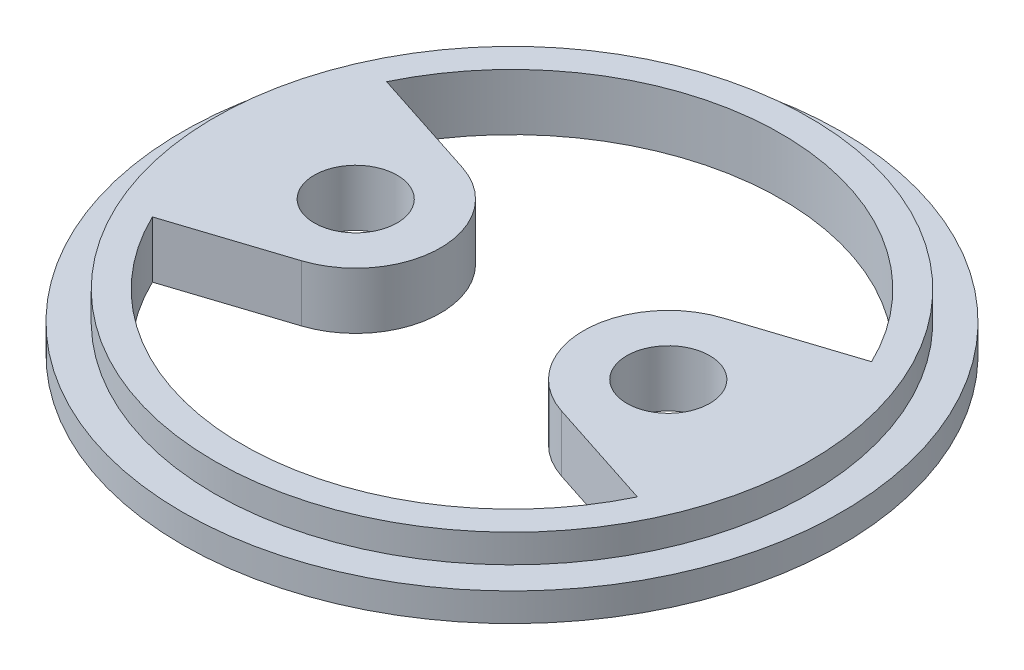
SolidWorks part; units mm, degrees
ref_plane "Front Plane" through (0, 0, 0) normal (0, 0, 1) x (1, 0, 0)
ref_plane "Top Plane" through (0, 0, 0) normal (0, 1, 0) x (1, 0, 0)
ref_plane "Right Plane" through (0, 0, 0) normal (1, 0, 0) x (0, 0, -1)
sketch "Sketch2" plane through (0, 0, 0) normal (0, 1, 0) x (1, 0, 0)
  line L0 (-8.3, 0) -> (0, 0) construction
  line L4 (0, 0) -> (0, 18.8683) construction
  line L7 (0, 0) -> (8.3, 0) construction
  circle A0 centre (0, 0) radius 17.5
  circle A3 centre (-8.3, 0) radius 2.2
  circle A4 centre (8.3, 0) radius 2.2
  dimension "D1" = 8.3
  dimension "D2" = 35
  dimension "D3" = 4.4
extrude "Boss-Extrude2" add sketch "Sketch2" along normal blind 3
sketch "Sketch3" plane through (0, 3, 0) normal (0, 1, 0) x (1, 0, 0)
  circle A0 centre (0, 0) radius 15.8
  dimension "D1" = 31.6
extrude "Cut-Extrude1" cut sketch "Sketch3" against normal blind 1.5 flip side to cut
sketch "Sketch4" plane through (0, 3, 0) normal (0, 1, 0) x (1, 0, 0)
  line L0 (-22.2573, 0) -> (20.184, 0) construction
  line L1 (-6.9094, 4.2798) -> (-6.9094, -4.2798) construction
  line L2 (-6.9094, -4.2798) -> (-12.877, -6.2187)
  line L3 (-6.9094, 4.2798) -> (-12.877, 6.2187)
  line L4 (0, 10.9333) -> (0, -10.9375) construction
  line L5 (6.9094, -4.2798) -> (12.877, -6.2187)
  line L6 (6.9094, 4.2798) -> (12.877, 6.2187)
  circle A0 centre (0, 0) radius 14.3
  arc A1 (-6.9094, 4.2798) -> (-6.9094, -4.2798) centre (-8.3, 0) cw
  arc A2 (6.9094, 4.2798) -> (6.9094, -4.2798) centre (8.3, 0) ccw
  dimension "D1" = 28.6
  dimension "D2" = 4.5
  dimension "D3" = 18
extrude "Cut-Extrude2" cut sketch "Sketch4" against normal through all contours A2 L6 A0 L3 A1 L2 L5
